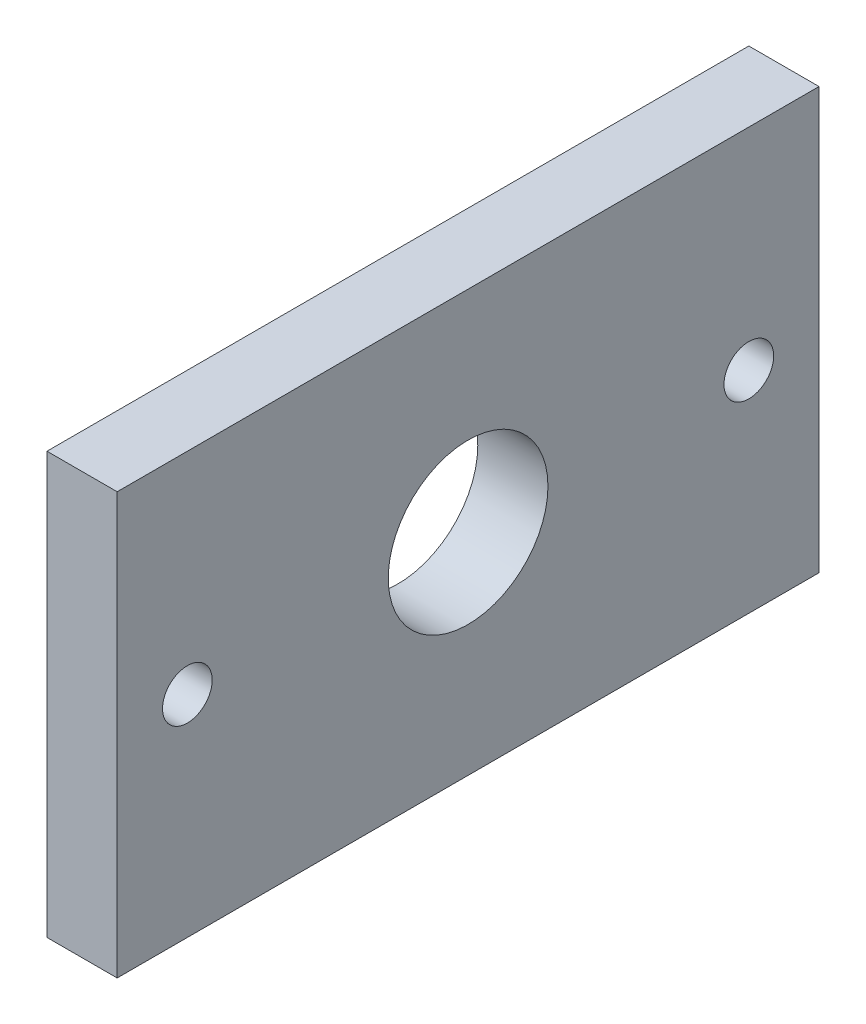
SolidWorks part; units mm, degrees
material "1060 Alloy"
ref_plane "Front Plane" through (0, 0, 0) normal (0, 0, 1) x (1, 0, 0)
ref_plane "Top Plane" through (0, 0, 0) normal (0, 1, 0) x (1, 0, 0)
ref_plane "Right Plane" through (0, 0, 0) normal (1, 0, 0) x (0, 0, -1)
sketch "Sketch1" plane through (0, 0, 0) normal (1, 0, 0) x (0, 0, -1)
  line L0 (0, 19.05) -> (0, -19.05) construction
  line L1 (-31.75, -19.05) -> (31.75, -19.05)
  line L2 (-31.75, -19.05) -> (-31.75, 19.05)
  line L3 (-31.75, 19.05) -> (31.75, 19.05)
  line L4 (31.75, -19.05) -> (31.75, 19.05)
  line L5 (-31.75, -19.05) -> (31.75, 19.05) construction
  line L6 (-31.75, 19.05) -> (31.75, -19.05) construction
  circle A0 centre (0, 0) radius 7.2263
  circle A1 centre (-25.4, 0) radius 2.2479
  circle A2 centre (25.4, 0) radius 2.2479
  point P0 (0, 0)
  dimension "D3" = 14.4526
  dimension "D4" = 4.4958
  dimension "D5" = 25.4
  dimension "D1" = 38.1
  dimension "D2" = 63.5
extrude "Boss-Extrude1" add sketch "Sketch1" along normal blind 6.35
